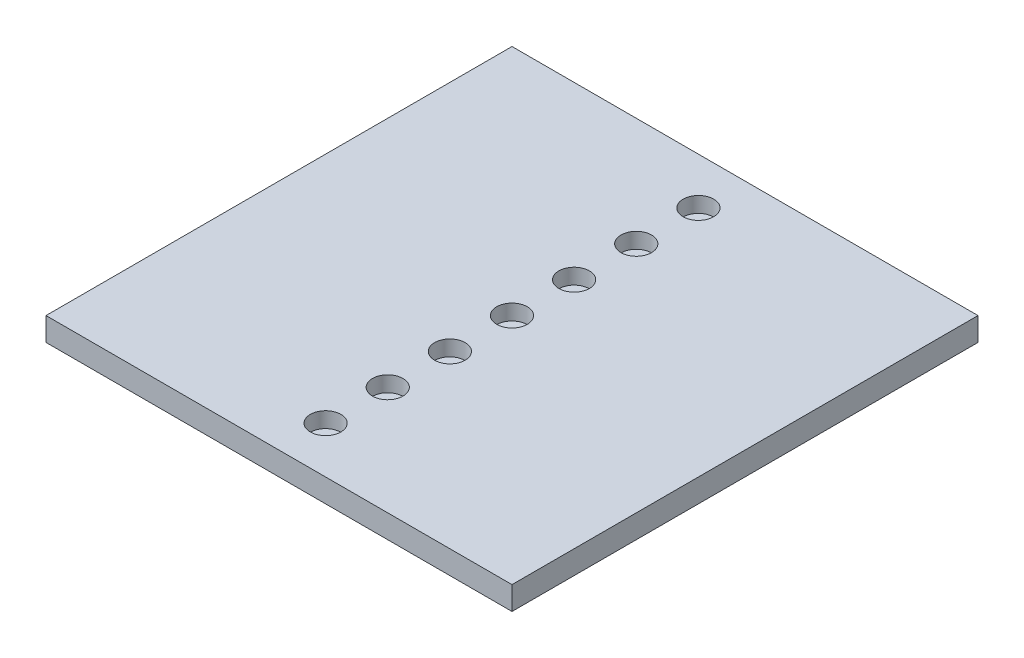
SolidWorks part; units mm, degrees
ref_plane "Front" through (0, 0, 0) normal (0, 0, 1) x (1, 0, 0)
ref_plane "Top" through (0, 0, 0) normal (0, 1, 0) x (1, 0, 0)
ref_plane "Right" through (0, 0, 0) normal (1, 0, 0) x (0, 0, -1)
sketch "Sketch2" plane through (0, 0, 0) normal (0, 1, 0) x (1, 0, 0)
  line L0 (0, 190.5) -> (0, -190.5) construction
  line L1 (-190.5, 190.5) -> (190.5, 190.5)
  line L2 (-190.5, 190.5) -> (-190.5, -190.5)
  line L3 (-190.5, -190.5) -> (190.5, -190.5)
  line L4 (190.5, 190.5) -> (190.5, -190.5)
  line L5 (-190.5, 190.5) -> (190.5, -190.5) construction
  line L6 (-190.5, -190.5) -> (190.5, 190.5) construction
  line L7 (0, 0) -> (0, 50.8) construction
  circle A0 centre (0, 0) radius 3.3782
  circle A1 centre (0, 50.8) radius 3.3782
  circle A2 centre (0, 101.6) radius 3.3782
  circle A3 centre (0, 152.4) radius 3.3782
  circle A4 centre (0, -50.8) radius 3.3782
  circle A5 centre (0, -101.6) radius 3.3782
  circle A6 centre (0, -152.4) radius 3.3782
  point P0 (0, 0)
  point P9 (0, 0)
  dimension "D2" = 6.7564
  dimension "D1" = 381
  dimension "D3" = 4
  dimension "D4" = 50.8
  dimension "D5" = 4
extrude "Bolt Holes" add sketch "Sketch2" along normal blind 19.05
sketch "Sketch3" plane through (0, 19.05, 0) normal (0, 1, 0) x (1, 0, 0)
  circle A0 centre (0, -50.8) radius 12.5
  circle A1 centre (0, 0) radius 12.5
  circle A2 centre (0, -101.6) radius 12.5
  circle A3 centre (0, 50.8) radius 12.5
  circle A4 centre (0, 101.6) radius 12.5
  circle A5 centre (0, 152.4) radius 12.5
  circle A6 centre (0, -152.4) radius 12.5
  dimension "D1" = 25
extrude "Counterbore" cut sketch "Sketch3" against normal blind 12.7
